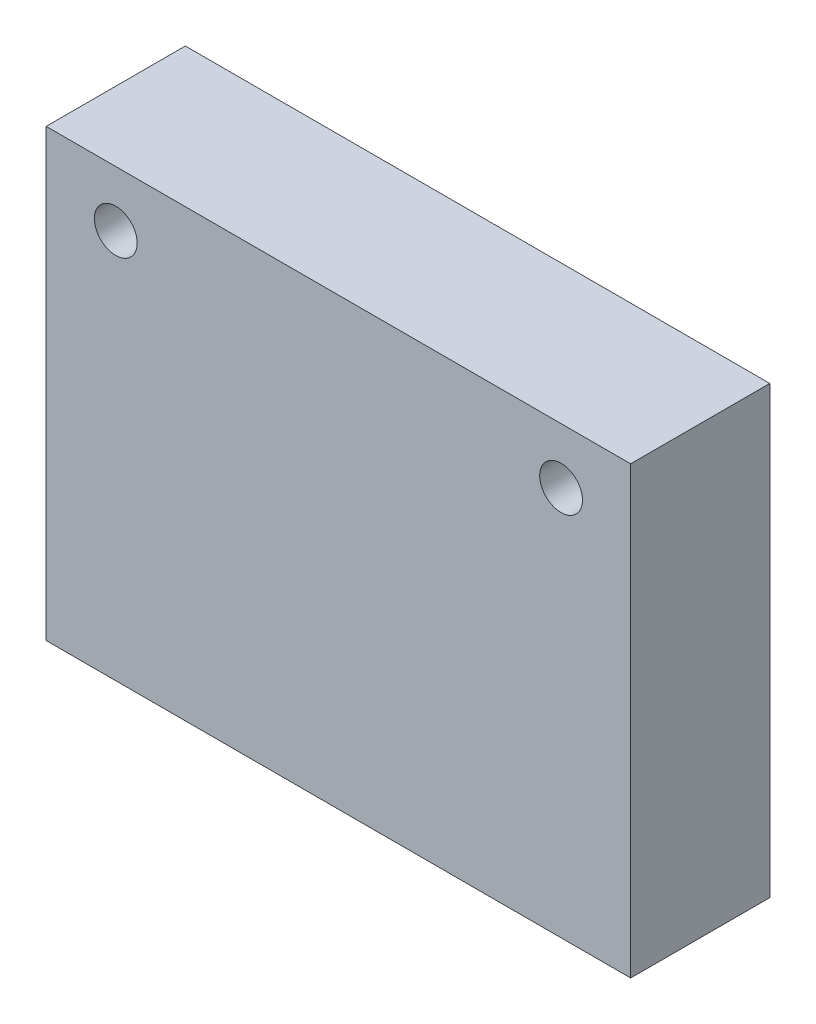
SolidWorks part; units mm, degrees
ref_plane "Alzado" through (0, 0, 0) normal (0, 0, 1) x (1, 0, 0)
ref_plane "Planta" through (0, 0, 0) normal (0, 1, 0) x (1, 0, 0)
ref_plane "Vista lateral" through (0, 0, 0) normal (1, 0, 0) x (0, 0, -1)
ref_plane "Plane1" through (0, 0, 0) normal (0, 0, -1) x (-1, 0, 0)
sketch "Sketch1" plane through (0, 0, 0) normal (0, 0, -1) x (-1, 0, 0)
  line L0 (-10.5, 8) -> (-10.5, -8)
  line L1 (-10.5, -8) -> (10.5, -8)
  line L2 (10.5, -8) -> (10.5, 8)
  line L3 (10.5, 8) -> (-10.5, 8)
  line L4 (0, 8) -> (0, -8) construction
  line L5 (-10.5, 0) -> (10.5, 0) construction
  line L6 (-8, 6) -> (8, 6) construction
  line L7 (-10.5, 8) -> (10.5, -8) construction
  line L8 (10.5, 8) -> (-10.5, -8) construction
  circle A0 centre (-8, 6) radius 0.7679
  circle A1 centre (8, 6) radius 0.7679
  point P12 (0, 0)
  dimension "D1" = 21
  dimension "D2" = 16
  dimension "D3" = 16
  dimension "D4" = 8
  dimension "D5" = 6
extrude "Boss-Extrude1" add sketch "Sketch1" against normal blind 5
